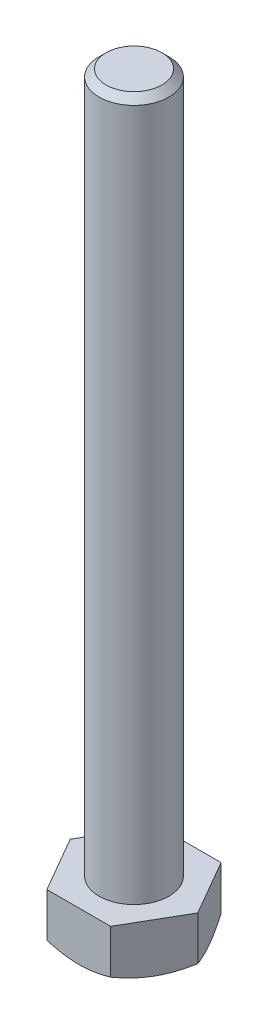
SolidWorks part; units mm, degrees
ref_plane "Front Plane" through (0, 0, 0) normal (0, 0, 1) x (1, 0, 0)
ref_plane "Top Plane" through (0, 0, 0) normal (0, 1, 0) x (1, 0, 0)
ref_plane "Right Plane" through (0, 0, 0) normal (1, 0, 0) x (0, 0, -1)
sketch "Sketch1" plane through (0, 0, 0) normal (0, 1, 0) x (1, 0, 0)
  line L1 (4.5611, 0) -> (2.2805, 3.95)
  line L2 (2.2805, 3.95) -> (-2.2805, 3.95)
  line L3 (-2.2805, 3.95) -> (-4.5611, 0)
  line L4 (-4.5611, 0) -> (-2.2805, -3.95)
  line L5 (-2.2805, -3.95) -> (2.2805, -3.95)
  line L6 (2.2805, -3.95) -> (4.5611, 0)
  circle A0 centre (0, 0) radius 3.95 construction
  dimension "D1" = 7.9
extrude "Boss-Extrude1" add sketch "Sketch1" along normal blind 53.5
sketch "Sketch2" plane through (0, 53.5, 0) normal (0, 1, 0) x (1, 0, 0)
  circle A0 centre (0, 0) radius 2.5
  dimension "D1" = 5
extrude "Cut-Extrude1" cut sketch "Sketch2" against normal blind 50 flip side to cut
sketch "Sketch3" plane through (0, 0, 0) normal (1, 0, 0) x (0, 0, -1)
  line L0 (3.95, 0) -> (5.249, 0.75)
  line L1 (5.249, 0.75) -> (5.249, -0.75)
  line L2 (5.249, -0.75) -> (3.95, 0)
  dimension "D1" = 1.5
ref_axis "Axis1" through (0, 3.5, 0) along (0, 1, 0)
revolve "Cut-Revolve1" cut sketch "Sketch3" angle 360 about axis through (0, 3.5, 0) along (0, 1, 0)
chamfer "Chamfer1" distance 0.5 angle 45 1 edges at (0, 53.5, 2.5)
sketch "Sketch5" plane through (0, 53.5, 0) normal (0, 1, 0) x (1, 0, 0)
  circle A0 centre (0, 0) radius 3
  dimension "D1" = 6
curve "Helix/Spiral1" pitch 0.7 height 46 turns 65.7143
ref_plane "Plane1" through (0, 53.5, 3) normal (-0.9993, -0.0371, 0) x (0, 0, 1)
